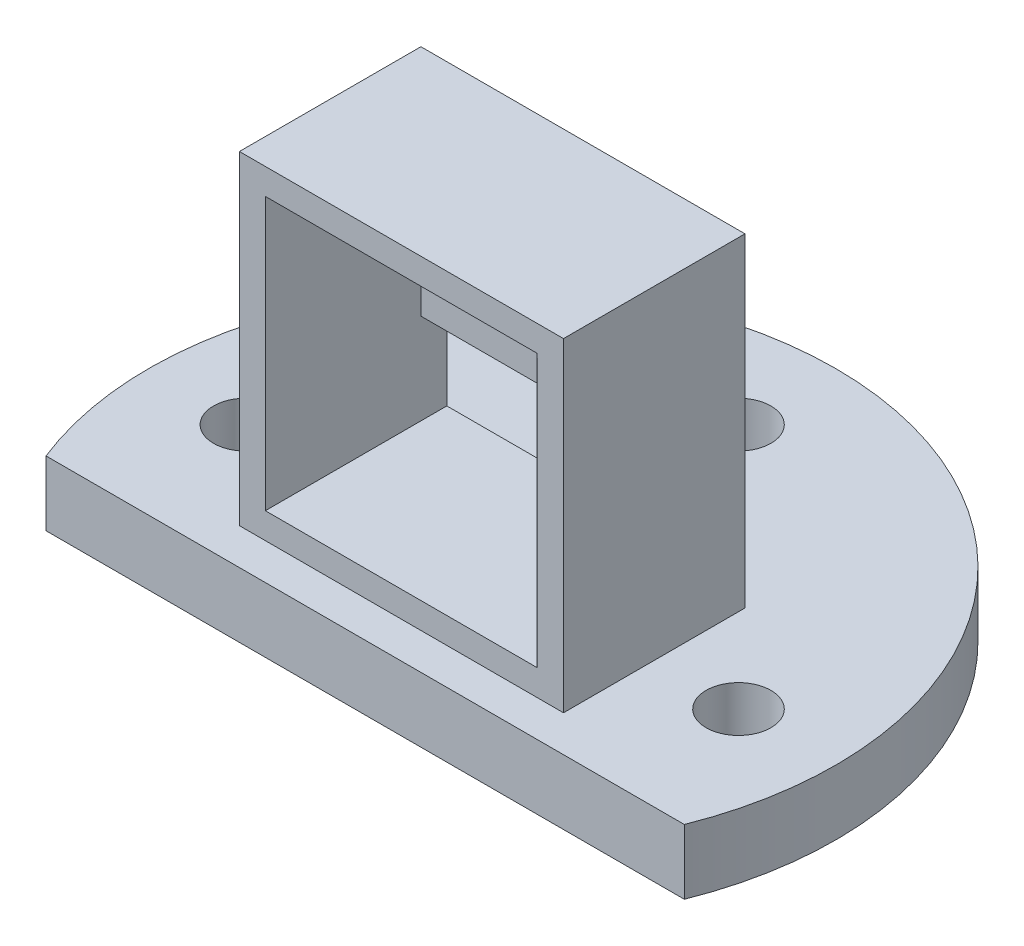
SolidWorks part; units mm, degrees
ref_plane "Front Plane" through (0, 0, 0) normal (0, 0, 1) x (1, 0, 0)
ref_plane "Top Plane" through (0, 0, 0) normal (0, 1, 0) x (1, 0, 0)
ref_plane "Right Plane" through (0, 0, 0) normal (1, 0, 0) x (0, 0, -1)
sketch "Sketch1" plane through (0, 0, 0) normal (0, 1, 0) x (1, 0, 0)
  line L0 (-49.2429, -19.5995) -> (49.2429, -19.5995)
  arc A0 (49.2429, -19.5995) -> (-49.2429, -19.5995) centre (0, 0) ccw
  circle A1 centre (-38, 0) radius 5
  circle A2 centre (38, 0) radius 5
  circle A3 centre (0, 38) radius 5
  point P10 (-103.6863, 2.5425)
  point P11 (0, 0)
extrude "Boss-Extrude4" add sketch "Sketch1" along normal blind 10
sketch "Sketch5" plane through (0, 10, 0) normal (0, 1, 0) x (1, 0, 0)
  line L1 (-25, -14) -> (25, -14)
  line L2 (-25, -14) -> (-25, 14)
  line L3 (-25, 14) -> (25, 14)
  line L4 (25, -14) -> (25, 14)
extrude "Boss-Extrude5" add sketch "Sketch5" along normal blind 50 contours L2 L1 L4 L3
sketch "Sketch6" plane through (0, 0, 14) normal (0, 0, 1) x (1, 0, 0)
  line L1 (-21, 14) -> (21, 14)
  line L2 (-21, 14) -> (-21, 56)
  line L3 (-21, 56) -> (21, 56)
  line L4 (21, 14) -> (21, 56)
extrude "Boss-Extrude7" add sketch "Sketch6" against normal blind 24 separate body contours L2 L1 L4 L3
sketch "Sketch9" plane through (0, 0, 14) normal (0, 0, 1) x (1, 0, 0)
  line L1 (-21, 56) -> (20.8929, 56)
  line L2 (-21, 56) -> (-21, 14)
  line L3 (-21, 14) -> (20.8929, 14)
  line L4 (20.8929, 56) -> (20.8929, 14)
extrude "Cut-Extrude1" cut sketch "Sketch9" against normal blind 24
sketch "Sketch10" plane through (0, 0, -10) normal (0, 0, 1) x (1, 0, 0)
  line L0 (-21, 56) -> (-21, 14) construction
  line L1 (-21, 44) -> (20.8929, 44)
  line L2 (-21, 44) -> (-21, 56)
  line L3 (-21, 56) -> (20.8929, 56)
  line L4 (20.8929, 44) -> (20.8929, 56)
  line L5 (-21, 56) -> (-21, 14) construction
  line L6 (20.8929, 14) -> (20.8929, 56) construction
  point P4 (22.3304, 53.0492)
  point P5 (-18.8802, 53.2409)
  point P6 (-21, 56)
  point P11 (20.8929, 43.3695)
  point P14 (0, 0)
  point P15 (0, 0)
extrude "Cut-Extrude6" cut sketch "Sketch10" against normal blind 4
sketch "Sketch11" plane through (0, 0, -10) normal (0, 0, 1) x (1, 0, 0)
  line L0 (20.8929, 14) -> (20.8929, 44) construction
  line L1 (-21, 14) -> (20.8929, 14)
  line L2 (-21, 14) -> (-21, 28)
  line L3 (-21, 28) -> (20.8929, 28)
  line L4 (20.8929, 14) -> (20.8929, 28)
extrude "Cut-Extrude7" cut sketch "Sketch11" against normal blind 4
